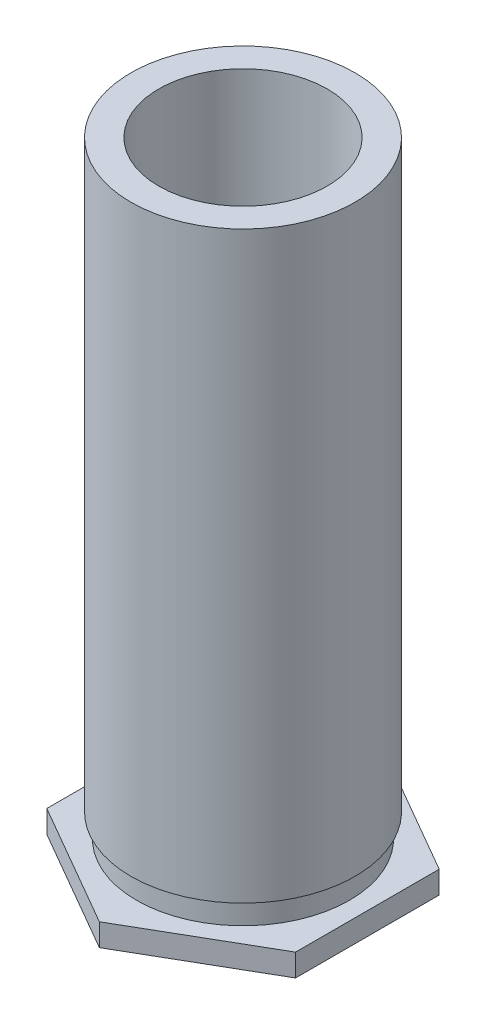
SolidWorks part; units mm, degrees
revolve "Body" add sketch "BodySke"
sketch "BodySke" plane through (0, 0, 0) normal (0, 0, 1) x (1, 0, 0)
  line L0 (3.56, 0) -> (4.582, 0)
  line L1 (4.582, 0) -> (4.582, 0.712)
  line L2 (4.582, 0.712) -> (3.382, 0.712)
  line L3 (2.1, 20) -> (2.1, 0.006)
  line L4 (3.56, 1.4596) -> (3.382, 1.4596)
  line L5 (3.382, 1.4596) -> (3.382, 0.712)
  line L6 (3.56, 0.0025) -> (3.56, 0)
  line L7 (1.016, 19.2) -> (3.6522, 19.2) construction
  line L8 (3.56, 20) -> (2.1, 20)
  line L9 (0, 0) -> (0, 15.24) construction
  line L10 (3.56, 0.0025) -> (0, 0.0025)
  line L11 (3.56, 20) -> (3.56, 1.4596)
  line L12 (0, 0.006) -> (2.1, 0.006)
  line L13 (0, 0.006) -> (0, 0.0025)
  line L14 (1.016, 0.006) -> (3.6522, 0.006) construction
  line L15 (1.016, 0) -> (3.6522, 0) construction
  dimension "E_dia" = 9.164
  dimension "Thread_min" = 4.2
  dimension "C_dia" = 7.12
  dimension "Thread_limit" = 19.994
  dimension "Advance" = 0.8
  dimension "Thread_depth" = 19.994
  dimension "Drill_depth" = 20
  dimension "Length" = 20
  dimension "Clinching_ht" = 0.712
  dimension "Groove_wid" = 0.7476
  dimension "Groove_dia" = 6.764
  dimension "D1" = 0.0025
cosmetic thread "ThreadCosmetic" [suppressed]
revolve "EndChamfer" cut sketch "EndChamferSke" angle 360 about L0
sketch "EndChamferSke" plane through (0, 0, 0) normal (0, 0, 1) x (1, 0, 0)
  line L0 (0, -2.54) -> (0, 7.62) construction
  line L1 (0, 0) -> (0, 15.24) construction
  line L2 (2.675, 12) -> (2.675, 20.254)
  line L4 (2.675, 12) -> (2.5, 12)
  line L6 (2.5, 12) -> (2.1, 11.72)
  line L8 (2.1, 11.72) -> (2.1, 20.254)
  line L9 (2.675, 20.254) -> (2.1, 20.254)
  line L10 (3.56, 20) -> (-3.56, 20) construction
  dimension "D1" = 0.254
  dimension "Thread_nominal" = 5
  dimension "D2" = 34.99
  dimension "Thread_min" = 4.2
  dimension "Inset" = 8
  dimension "B_dia" = 5.35
revolve "TapDrill" cut sketch "TapDriSke" angle 360 about L0
sketch "TapDriSke" plane through (0, 0, 0) normal (0, 0, 1) x (1, 0, 0)
  line L0 (0, 0) -> (0, 15.24) construction
  line L1 (0, 0) -> (0, 15.24) construction
  line L2 (2.1, -3.994) -> (2.1, 20)
  line L3 (3.56, 20) -> (-3.56, 20) construction
  line L4 (2.1, -3.994) -> (0, -4.8638)
  line L5 (0, -4.8638) -> (0, 20)
  line L6 (0, 20) -> (2.1, 20)
  line L7 (2.1, 0.006) -> (2.1, 20) construction
  line L8 (0, -4.8638) -> (-2.1, -3.994) construction
  line L9 (-2.1, 20) -> (-2.1, 0.006) construction
  dimension "D1" = 135
ref_plane "Plane1" through (0, 0, 0) normal (0, 0, 1) x (1, 0, 0)
ref_plane "Plane2" through (0, 0, 0) normal (0, 1, 0) x (1, 0, 0)
ref_plane "Plane3" through (0, 0, 0) normal (1, 0, 0) x (0, 0, -1)
ref_plane "Plane4" through (0, -0.5486, 0) normal (0, 1, 0) x (-1, 0, 0)
sketch "ThdSchSke" plane through (0, 0, 0) normal (0, 0, 1) x (1, 0, 0)
  line L0 (0, -5.08) -> (0, 7.62) construction
  line L1 (0, 0) -> (0, 15.24) construction
  line L2 (0, 12) -> (2.5, 12) construction
  line L4 (2.5, 12) -> (2.1, 12.2801)
  line L5 (2.675, 12) -> (-2.675, 12) construction
  line L6 (2.5, 12) -> (2.1, 11.7199)
  line L7 (2.1, 12.2801) -> (2.1, 11.7199)
  dimension "Thread_min" = 4.2
revolve "ThreadSchematic" cut sketch "ThdSchSke" angle 360 about L0
pattern_linear "ThdSchPat" count 16 spacing 0.7996 along (0, -1, 0) of "ThreadSchematic"
sketch "HexDieSke" plane through (0, 0.712, 0) normal (0, 1, 0) x (-1, 0, 0)
  line L0 (0, 4.5611) -> (3.95, 2.2805)
  line L1 (3.95, 2.2805) -> (3.95, -2.2805)
  line L2 (3.95, -2.2805) -> (0, -4.5611)
  line L3 (0, -4.5611) -> (-3.95, -2.2805)
  line L4 (-3.95, -2.2805) -> (-3.95, 2.2805)
  line L5 (-3.95, 2.2805) -> (0, 4.5611)
  circle A1 centre (0, 0) radius 3.95 construction
  circle A2 centre (0, 0) radius 4.5611 construction
  circle A3 centre (0, 0) radius 4.5825
  dimension "Width_across_flats" = 7.9
  dimension "OD" = 9.165
extrude "HexDie" cut sketch "HexDieSke" against normal blind 0.712
equation "' \"Length@BodySke\" = 20"
equation "' \"B_dia@EndChamferSke\" = 5.35"
equation "' \"C_dia@BodySke\" = 7.12"
equation "' \"Width_across_flats@HexDieSke\" = 7.9"
equation "' \"Inset@EndChamferSke\" = 8"
equation "' \"Advance@BodySke\" = 0.8"
equation "' \"Thread_min@BodySke\" = 4.2"
equation "' \"Thread_nominal@ThreadCosmetic\" = 5"
equation "\"E_dia@BodySke\" = \"Width_across_flats@HexDieSke\" * 1.16"
equation "\"Drill_depth@BodySke\" = \"Length@BodySke\""
equation "\"Thread_depth@BodySke\" = \"Length@BodySke\" - 0.006"
equation "\"Clinching_ht@BodySke\" = \"C_dia@BodySke\" * 0.1"
equation "\"Groove_dia@BodySke\" = \"C_dia@BodySke\" * 0.95"
equation "\"Groove_wid@BodySke\" = \"Clinching_ht@BodySke\" * 1.05"
equation "\"Thread_limit@BodySke\" = ((sgn( \"Length@BodySke\" - \"Thread_depth@BodySke\" )-1)*( \"Length@BodySke\" - \"Thread_depth@BodySke\" ))/-2+ \"Thread_depth@BodySke\""
equation "\"Depth@TapDriSke\" = \"Thread_limit@BodySke\" + \"Advance@BodySke\" * 5"
equation "\"Depth@TapDriSke\" = ((sgn( \"Depth@TapDriSke\" - \"Drill_depth@BodySke\" )+1)*( \"Depth@TapDriSke\" - \"Drill_depth@BodySke\" ))/2 +\"Drill_depth@BodySke\""
equation "\"Depth@HexDie\" = \"Clinching_ht@BodySke\""
equation "\"OD@HexDieSke\" =  \"Width_across_flats@HexDieSke\" * 1.16 + 0.001"
equation "\"Thread_nominal@EndChamferSke\" = \"Thread_nominal@ThreadCosmetic\""
equation "\"Thread_min@EndChamferSke\" = \"Thread_min@BodySke\""
equation "\"D2@EndChamferSke\" = \"Vee_angle@ThdSchSke\" / 2 - 0.01"
equation "\"Thread_nominal@ThdSchSke\" = \"Thread_nominal@ThreadCosmetic\""
equation "\"Thread_min@ThdSchSke\" = \"Thread_min@BodySke\""
equation "\"Num_threads@ThdSchPat\" = int(  ( \"Thread_limit@BodySke\" - \"Inset@EndChamferSke\" ) / \"Advance@BodySke\" + 0.999 )  + 1"
equation "\"Advance@ThdSchPat\" = (  \"Thread_limit@BodySke\" - \"Inset@EndChamferSke\" ) /  (\"Num_threads@ThdSchPat\" - 1) 'relax it"
